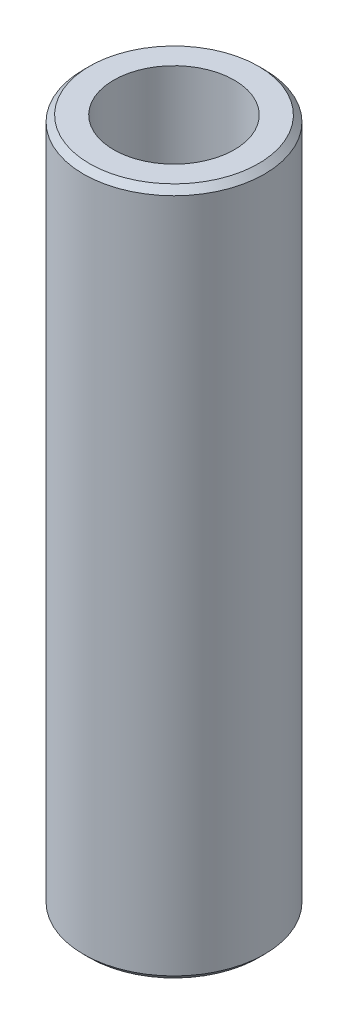
SolidWorks part; units mm, degrees
ref_plane "Front Plane" through (0, 0, 0) normal (0, 0, 1) x (1, 0, 0)
ref_plane "Top Plane" through (0, 0, 0) normal (0, 1, 0) x (1, 0, 0)
ref_plane "Right Plane" through (0, 0, 0) normal (1, 0, 0) x (0, 0, -1)
sketch "Sketch1" plane through (0, 0, 0) normal (0, 1, 0) x (1, 0, 0)
  circle A0 centre (0, 0) radius 5
  circle A1 centre (0, 0) radius 7.5
  dimension "D1" = 10
  dimension "D2" = 15
extrude "Corpo Ø15×57" add sketch "Sketch1" along normal blind 57
chamfer "Chanfros 0.5×45°" distance 0.5 angle 45 2 edges at (0, 0, 7.5) (0, 57, 7.5)
